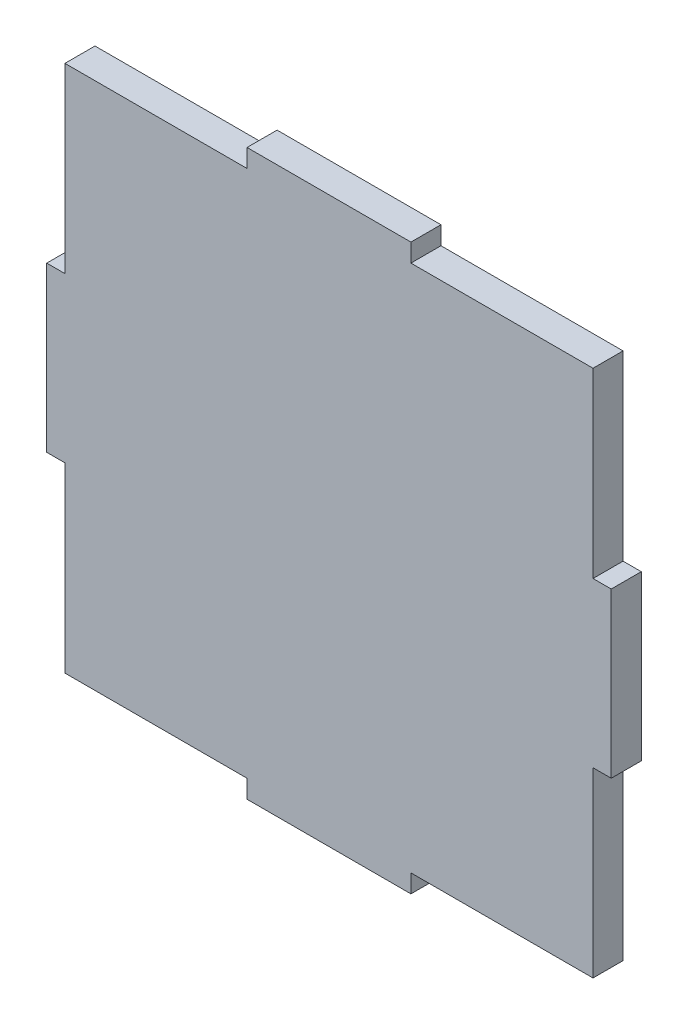
SolidWorks part; units mm, degrees
ref_plane "Front Plane" through (0, 0, 0) normal (0, 0, 1) x (1, 0, 0)
ref_plane "Top Plane" through (0, 0, 0) normal (0, 1, 0) x (1, 0, 0)
ref_plane "Right Plane" through (0, 0, 0) normal (1, 0, 0) x (0, 0, -1)
sketch "Sketch1" plane through (0, 0, 0) normal (0, 0, 1) x (1, 0, 0)
  line L1 (0, 0) -> (31, 0)
  line L2 (0, 0) -> (0, 31)
  line L3 (0, 31) -> (31, 31)
  line L4 (31, 0) -> (31, 31)
  line L5 (1, 1) -> (30, 1)
  line L6 (1, 1) -> (1, 30)
  line L7 (1, 30) -> (30, 30)
  line L8 (30, 1) -> (30, 30)
  line L9 (0, 20) -> (1, 20)
  line L10 (0, 20) -> (0, 11)
  line L11 (0, 11) -> (1, 11)
  line L12 (1, 20) -> (1, 11)
  line L13 (11, 31) -> (20, 31)
  line L14 (11, 31) -> (11, 30)
  line L15 (11, 30) -> (20, 30)
  line L16 (20, 31) -> (20, 30)
  line L17 (30, 20) -> (31, 20)
  line L18 (30, 20) -> (30, 11)
  line L19 (30, 11) -> (31, 11)
  line L20 (31, 20) -> (31, 11)
  line L21 (11, 1) -> (20, 1)
  line L22 (11, 1) -> (11, 0)
  line L23 (11, 0) -> (20, 0)
  line L24 (20, 1) -> (20, 0)
  dimension "D1" = 31
  dimension "D2" = 31
  dimension "D3" = 29
  dimension "D4" = 29
  dimension "D5" = 1
  dimension "D6" = 1
  dimension "D7" = 10
  dimension "D8" = 9
  dimension "D9" = 10
  dimension "D10" = 9
  dimension "D11" = 10
  dimension "D12" = 9
  dimension "D13" = 10
  dimension "D14" = 9
extrude "Boss-Extrude1" add sketch "Sketch1" along normal blind 1.65 contours L5 L8 L7 L6 | L2 L11 L6 L9 | L16 L3 L14 L7 | L8 L19 L4 L17 | L24 L5 L22 L1
